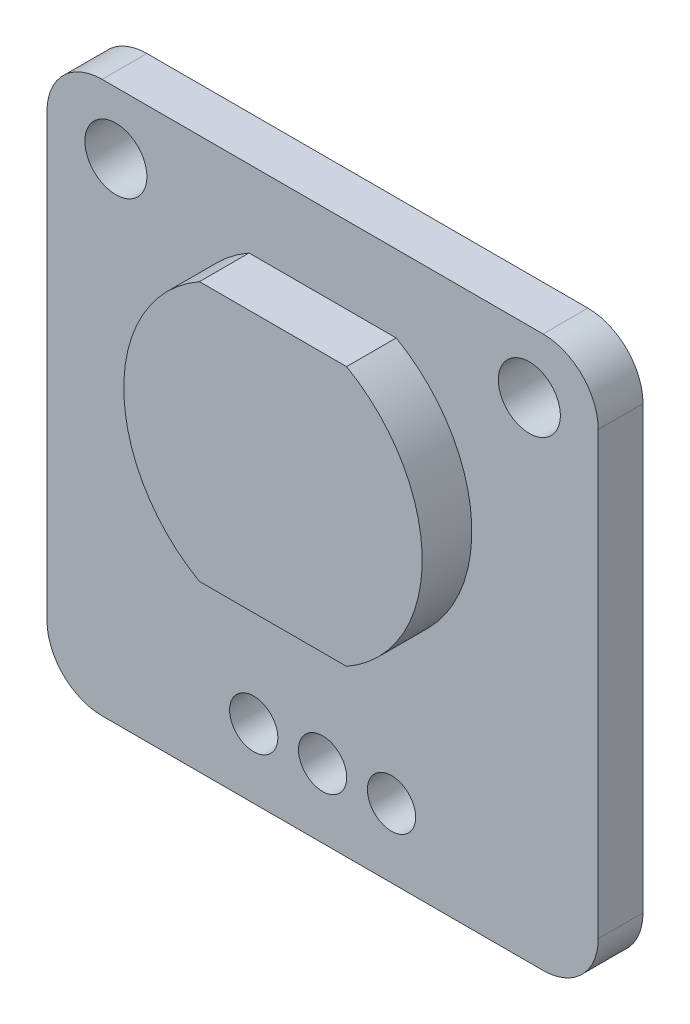
SolidWorks part; units mm, degrees
ref_plane "Front Plane" through (0, 0, 0) normal (0, 0, 1) x (1, 0, 0)
ref_plane "Top Plane" through (0, 0, 0) normal (0, 1, 0) x (1, 0, 0)
ref_plane "Right Plane" through (0, 0, 0) normal (1, 0, 0) x (0, 0, -1)
sketch "Sketch1" plane through (0, 0, 0) normal (0, 0, 1) x (1, 0, 0)
  line L1 (-8.0455, 11.0289) -> (8.2105, 11.0289)
  line L2 (-10.0775, 8.9969) -> (-10.0775, -7.2591)
  line L3 (-8.0455, -9.2911) -> (8.2105, -9.2911)
  line L4 (10.2425, 8.9969) -> (10.2425, -7.2591)
  arc A0 (8.2105, -9.2911) -> (10.2425, -7.2591) centre (8.2105, -7.2591) ccw
  arc A1 (-10.0775, -7.2591) -> (-8.0455, -9.2911) centre (-8.0455, -7.2591) ccw
  arc A2 (-8.0455, 11.0289) -> (-10.0775, 8.9969) centre (-8.0455, 8.9969) ccw
  arc A3 (8.2105, 11.0289) -> (10.2425, 8.9969) centre (8.2105, 8.9969) cw
  circle A4 centre (-7.5375, 8.7429) radius 1.143
  circle A5 centre (7.7025, 8.7429) radius 1.143
  circle A6 centre (0.0825, -6.7511) radius 0.889
  circle A7 centre (2.6225, -6.7511) radius 0.889
  circle A10 centre (-2.4575, -6.7511) radius 0.889
  circle A13 centre (5.1625, -6.7511) radius 0.889 [skipped]
  circle A14 centre (7.7025, -6.7511) radius 0.889 [skipped]
  circle A15 centre (-4.9975, -6.7511) radius 0.889 [skipped]
  circle A16 centre (-7.5375, -6.7511) radius 0.889 [skipped]
  point P6 (10.2425, -9.2911)
  point P11 (-10.0775, 11.0289)
  point P14 (10.2425, 11.0289)
  dimension "D3" = 2.032
  dimension "D4" = 2.54
  dimension "D5" = 2.54
  dimension "D6" = 2.286
  dimension "D7" = 2.54
  dimension "D1" = 20.32
  dimension "D2" = 20.32
  dimension "D8" = 2.286
  dimension "D9" = 4
  dimension "D10" = 4
extrude "Boss-Extrude1" add sketch "Sketch1" along normal blind 1.651
sketch "Sketch2" plane through (0, 0, 1.651) normal (0, 0, 1) x (1, 0, 0)
  line L0 (10.2425, -7.2591) -> (10.2425, 8.9969) construction
  line L1 (8.2105, 11.0289) -> (-8.0455, 11.0289) construction
  line L3 (2.7943, 8.1939) -> (-2.6293, 8.1939)
  line L5 (2.7943, -1.3761) -> (-2.6293, -1.3761)
  arc A0 (2.7943, -1.3761) -> (2.7943, 8.1939) centre (0.0825, 3.4089) ccw
  arc A1 (-2.6293, 8.1939) -> (-2.6293, -1.3761) centre (0.0825, 3.4089) ccw
  dimension "D1" = 10.16
  dimension "D2" = 7.62
  dimension "D3" = 11
  dimension "D4" = 9.57
extrude "Boss-Extrude2" add sketch "Sketch2" along normal blind 1.8288
